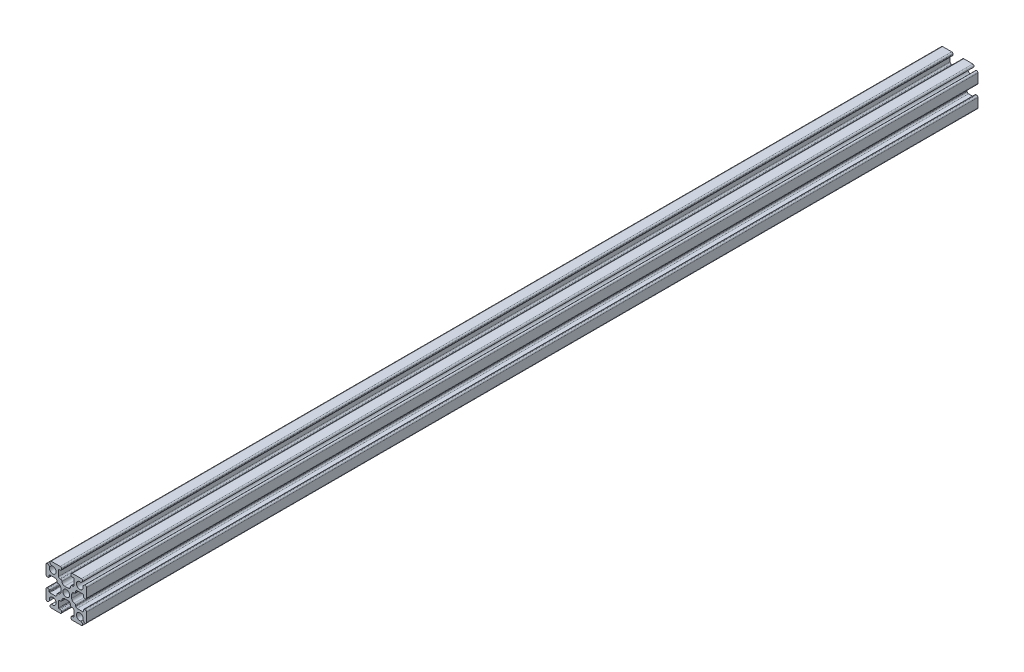
SolidWorks part; units mm, degrees
ref_plane "Front" through (0, 0, 0) normal (0, 0, 1) x (1, 0, 0)
ref_plane "Top" through (0, 0, 0) normal (0, 1, 0) x (1, 0, 0)
ref_plane "Right" through (0, 0, 0) normal (1, 0, 0) x (0, 0, -1)
sketch "Sketch1" plane through (0, 0, 0) normal (0, 0, 1) x (1, 0, 0)
  line L0 (6.6464, 5.9393) -> (6.1636, 5.4565)
  line L1 (5.4565, 6.1636) -> (5.9393, 6.6464)
  line L2 (5.5858, 7.5) -> (2.25, 7.5)
  line L3 (1.75, 7) -> (1.75, 6.8)
  line L4 (2.25, 6.3) -> (2.65, 6.3)
  line L5 (2.85, 6.1) -> (2.85, 4)
  line L6 (2.35, 3.5) -> (2.1, 3.5)
  line L7 (0.6, 2) -> (-0.6, 2)
  line L8 (-2.1, 3.5) -> (-2.35, 3.5)
  line L9 (-2.85, 4) -> (-2.85, 6.1)
  line L10 (-2.65, 6.3) -> (-2.25, 6.3)
  line L11 (-1.75, 6.8) -> (-1.75, 7)
  line L12 (-2.25, 7.5) -> (-5.5858, 7.5)
  line L13 (-5.9393, 6.6464) -> (-5.4565, 6.1636)
  line L14 (-6.1636, 5.4565) -> (-6.6464, 5.9393)
  line L15 (-7.5, 5.5858) -> (-7.5, 2.25)
  line L16 (-7, 1.75) -> (-6.8, 1.75)
  line L17 (-6.3, 2.25) -> (-6.3, 2.65)
  line L18 (-6.1, 2.85) -> (-4, 2.85)
  line L19 (-3.5, 2.35) -> (-3.5, 2.1)
  line L20 (-2, 0.6) -> (-2, -0.6)
  line L21 (-3.5, -2.1) -> (-3.5, -2.35)
  line L22 (-4, -2.85) -> (-6.1, -2.85)
  line L23 (-6.3, -2.65) -> (-6.3, -2.25)
  line L24 (-6.8, -1.75) -> (-7, -1.75)
  line L25 (-7.5, -2.25) -> (-7.5, -5.5858)
  line L26 (-6.6464, -5.9393) -> (-6.1636, -5.4565)
  line L27 (-5.4565, -6.1636) -> (-5.9393, -6.6464)
  line L28 (-5.5858, -7.5) -> (-2.25, -7.5)
  line L29 (-1.75, -7) -> (-1.75, -6.8)
  line L30 (-2.25, -6.3) -> (-2.65, -6.3)
  line L31 (-2.85, -6.1) -> (-2.85, -4)
  line L32 (-2.35, -3.5) -> (-2.1, -3.5)
  line L33 (-0.6, -2) -> (0.6, -2)
  line L34 (2.1, -3.5) -> (2.35, -3.5)
  line L35 (2.85, -4) -> (2.85, -6.1)
  line L36 (2.65, -6.3) -> (2.25, -6.3)
  line L37 (1.75, -6.8) -> (1.75, -7)
  line L38 (2.25, -7.5) -> (5.5858, -7.5)
  line L39 (5.9393, -6.6464) -> (5.4565, -6.1636)
  line L40 (6.1636, -5.4565) -> (6.6464, -5.9393)
  line L41 (7.5, -5.5858) -> (7.5, -2.25)
  line L42 (7, -1.75) -> (6.8, -1.75)
  line L43 (6.3, -2.25) -> (6.3, -2.65)
  line L44 (6.1, -2.85) -> (4, -2.85)
  line L45 (3.5, -2.35) -> (3.5, -2.1)
  line L46 (2, -0.6) -> (2, 0.6)
  line L47 (3.5, 2.1) -> (3.5, 2.35)
  line L48 (4, 2.85) -> (6.1, 2.85)
  line L49 (6.3, 2.65) -> (6.3, 2.25)
  line L50 (6.8, 1.75) -> (7, 1.75)
  line L51 (7.5, 2.25) -> (7.5, 5.5858)
  circle A0 centre (0, 0) radius 1.25
  arc A1 (6.1636, 5.4565) -> (5.4565, 6.1636) centre (5, 5) cw
  arc A2 (5.9393, 6.6464) -> (5.5858, 7.5) centre (5.5858, 7) ccw
  arc A3 (2.25, 7.5) -> (1.75, 7) centre (2.25, 7) ccw
  arc A4 (1.75, 6.8) -> (2.25, 6.3) centre (2.25, 6.8) ccw
  arc A5 (2.65, 6.3) -> (2.85, 6.1) centre (2.65, 6.1) cw
  arc A6 (2.85, 4) -> (2.35, 3.5) centre (2.35, 4) cw
  arc A7 (2.1, 3.5) -> (1.6, 3) centre (2.1, 3) ccw
  arc A8 (1.6, 3) -> (0.6, 2) centre (0.6, 3) cw
  arc A9 (-0.6, 2) -> (-1.6, 3) centre (-0.6, 3) cw
  arc A10 (-1.6, 3) -> (-2.1, 3.5) centre (-2.1, 3) ccw
  arc A11 (-2.35, 3.5) -> (-2.85, 4) centre (-2.35, 4) cw
  arc A12 (-2.85, 6.1) -> (-2.65, 6.3) centre (-2.65, 6.1) cw
  arc A13 (-2.25, 6.3) -> (-1.75, 6.8) centre (-2.25, 6.8) ccw
  arc A14 (-1.75, 7) -> (-2.25, 7.5) centre (-2.25, 7) ccw
  arc A15 (-5.5858, 7.5) -> (-5.9393, 6.6464) centre (-5.5858, 7) ccw
  arc A16 (-5.4565, 6.1636) -> (-6.1636, 5.4565) centre (-5, 5) cw
  arc A17 (-6.6464, 5.9393) -> (-7.5, 5.5858) centre (-7, 5.5858) ccw
  arc A18 (-7.5, 2.25) -> (-7, 1.75) centre (-7, 2.25) ccw
  arc A19 (-6.8, 1.75) -> (-6.3, 2.25) centre (-6.8, 2.25) ccw
  arc A20 (-6.3, 2.65) -> (-6.1, 2.85) centre (-6.1, 2.65) cw
  arc A21 (-4, 2.85) -> (-3.5, 2.35) centre (-4, 2.35) cw
  arc A22 (-3.5, 2.1) -> (-3, 1.6) centre (-3, 2.1) ccw
  arc A23 (-3, 1.6) -> (-2, 0.6) centre (-3, 0.6) cw
  arc A24 (-2, -0.6) -> (-3, -1.6) centre (-3, -0.6) cw
  arc A25 (-3, -1.6) -> (-3.5, -2.1) centre (-3, -2.1) ccw
  arc A26 (-3.5, -2.35) -> (-4, -2.85) centre (-4, -2.35) cw
  arc A27 (-6.1, -2.85) -> (-6.3, -2.65) centre (-6.1, -2.65) cw
  arc A28 (-6.3, -2.25) -> (-6.8, -1.75) centre (-6.8, -2.25) ccw
  arc A29 (-7, -1.75) -> (-7.5, -2.25) centre (-7, -2.25) ccw
  arc A30 (-7.5, -5.5858) -> (-6.6464, -5.9393) centre (-7, -5.5858) ccw
  arc A31 (-6.1636, -5.4565) -> (-5.4565, -6.1636) centre (-5, -5) cw
  arc A32 (-5.9393, -6.6464) -> (-5.5858, -7.5) centre (-5.5858, -7) ccw
  arc A33 (-2.25, -7.5) -> (-1.75, -7) centre (-2.25, -7) ccw
  arc A34 (-1.75, -6.8) -> (-2.25, -6.3) centre (-2.25, -6.8) ccw
  arc A35 (-2.65, -6.3) -> (-2.85, -6.1) centre (-2.65, -6.1) cw
  arc A36 (-2.85, -4) -> (-2.35, -3.5) centre (-2.35, -4) cw
  arc A37 (-2.1, -3.5) -> (-1.6, -3) centre (-2.1, -3) ccw
  arc A38 (-1.6, -3) -> (-0.6, -2) centre (-0.6, -3) cw
  arc A39 (0.6, -2) -> (1.6, -3) centre (0.6, -3) cw
  arc A40 (1.6, -3) -> (2.1, -3.5) centre (2.1, -3) ccw
  arc A41 (2.35, -3.5) -> (2.85, -4) centre (2.35, -4) cw
  arc A42 (2.85, -6.1) -> (2.65, -6.3) centre (2.65, -6.1) cw
  arc A43 (2.25, -6.3) -> (1.75, -6.8) centre (2.25, -6.8) ccw
  arc A44 (1.75, -7) -> (2.25, -7.5) centre (2.25, -7) ccw
  arc A45 (5.5858, -7.5) -> (5.9393, -6.6464) centre (5.5858, -7) ccw
  arc A46 (5.4565, -6.1636) -> (6.1636, -5.4565) centre (5, -5) cw
  arc A47 (6.6464, -5.9393) -> (7.5, -5.5858) centre (7, -5.5858) ccw
  arc A48 (7.5, -2.25) -> (7, -1.75) centre (7, -2.25) ccw
  arc A49 (6.8, -1.75) -> (6.3, -2.25) centre (6.8, -2.25) ccw
  arc A50 (6.3, -2.65) -> (6.1, -2.85) centre (6.1, -2.65) cw
  arc A51 (4, -2.85) -> (3.5, -2.35) centre (4, -2.35) cw
  arc A52 (3.5, -2.1) -> (3, -1.6) centre (3, -2.1) ccw
  arc A53 (3, -1.6) -> (2, -0.6) centre (3, -0.6) cw
  arc A54 (2, 0.6) -> (3, 1.6) centre (3, 0.6) cw
  arc A55 (3, 1.6) -> (3.5, 2.1) centre (3, 2.1) ccw
  arc A56 (3.5, 2.35) -> (4, 2.85) centre (4, 2.35) cw
  arc A57 (6.1, 2.85) -> (6.3, 2.65) centre (6.1, 2.65) cw
  arc A58 (6.3, 2.25) -> (6.8, 1.75) centre (6.8, 2.25) ccw
  arc A59 (7, 1.75) -> (7.5, 2.25) centre (7, 2.25) ccw
  arc A60 (7.5, 5.5858) -> (6.6464, 5.9393) centre (7, 5.5858) ccw
extrude "Boss-Extrude1" add sketch "Sketch1" along normal blind 330
